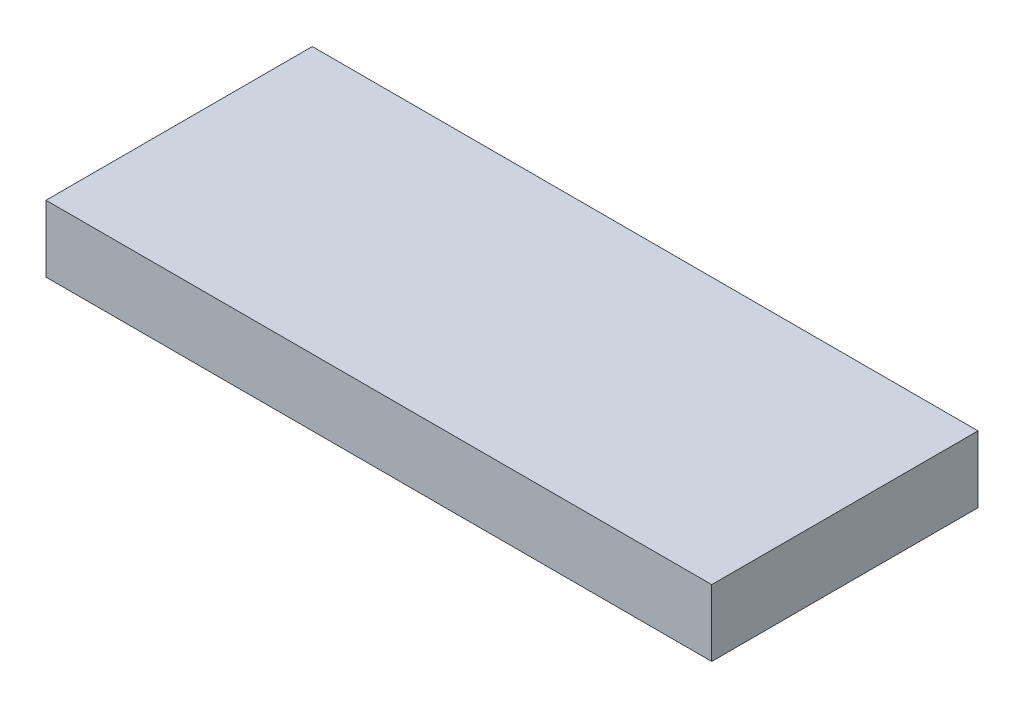
SolidWorks part; units mm, degrees
ref_plane "Front Plane" through (0, 0, 0) normal (0, 0, 1) x (1, 0, 0)
ref_plane "Top Plane" through (0, 0, 0) normal (0, 1, 0) x (1, 0, 0)
ref_plane "Right Plane" through (0, 0, 0) normal (1, 0, 0) x (0, 0, -1)
sketch "Sketch1" plane through (0, 0, 0) normal (0, 1, 0) x (1, 0, 0)
  line L1 (0, 0) -> (63.5, 0)
  line L2 (0, 0) -> (0, -25.4)
  line L3 (0, -25.4) -> (63.5, -25.4)
  line L4 (63.5, 0) -> (63.5, -25.4)
  dimension "D1" = 63.5
  dimension "D2" = 25.4
extrude "Boss-Extrude1" add sketch "Sketch1" along normal blind 6.35
sketch "Sketch2" plane through (0, 6.35, 0) normal (0, 1, 0) x (1, 0, 0)
  line L0 (63.5, -25.4) -> (63.5, 0) construction
  line L1 (0, -25.4) -> (63.5, -25.4) construction
  line L2 (63.5, 0) -> (0, 0) construction
  point P0 (34.036, -21.336)
  point P1 (34.036, -4.064)
  dimension "D1" = 29.464
  dimension "D2" = 29.464
  dimension "D3" = 4.064
  dimension "D4" = 4.064
